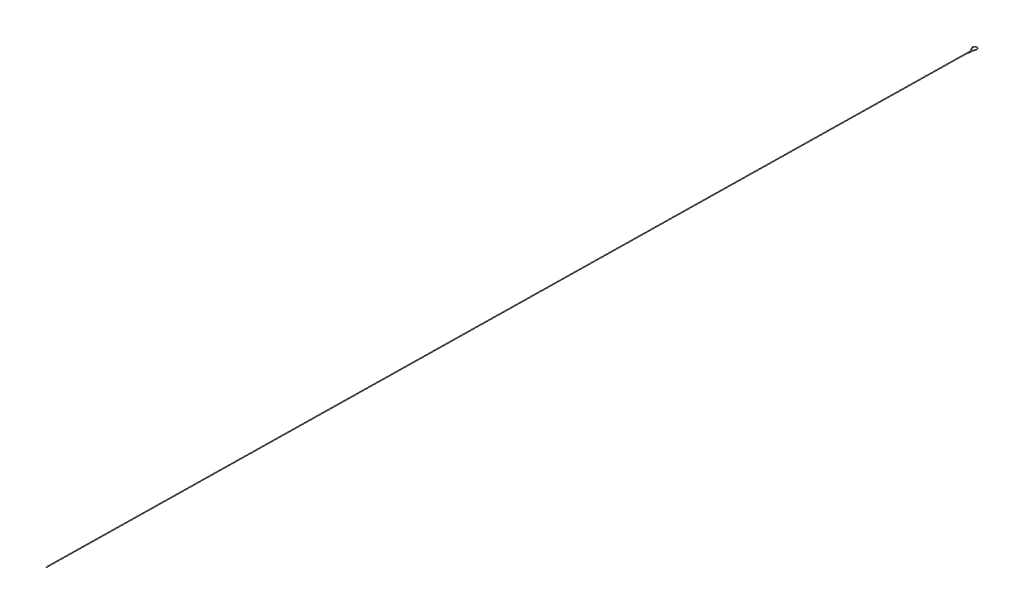
SolidWorks part; units mm, degrees
ref_plane "Front Plane" through (0, 0, 0) normal (0, 0, 1) x (1, 0, 0)
ref_plane "Top Plane" through (0, 0, 0) normal (0, 1, 0) x (1, 0, 0)
ref_plane "Right Plane" through (0, 0, 0) normal (1, 0, 0) x (0, 0, -1)
sketch "Sketch1" plane through (0, 0, 0) normal (0, 1, 0) x (1, 0, 0)
  line L0 (0, 4567.0606) -> (0, 4558.7974)
  line L2 (-10.4743, 4588.5976) -> (-1.2471, 4571.8965)
  line L3 (7.6178, 4589.0635) -> (4.4738, 4582.7755)
  line L4 (3.2, 4558.7974) -> (3.2, 4570.9408)
  line L5 (3.2, 4570.9408) -> (3.4223, 4578.5938)
  line L6 (0, 4558.7974) -> (0, 0) construction
  line L7 (0, 0) -> (-76.2, 0) construction
  line L8 (-76.2, 0) -> (-76.2, -10)
  line L9 (-76.2, 0) -> (0, 4558.7974)
  arc A0 (-4.9486, 4602.8985) -> (-3.0908, 4603.3788) centre (-0.8501, 4590.878) cw
  arc A1 (-3.0908, 4603.3788) -> (7.6178, 4589.0635) centre (-1.3265, 4593.5356) cw
  arc A2 (-4.9486, 4602.8985) -> (-10.4743, 4588.5976) centre (-1.7214, 4593.4335) ccw
  arc A5 (3.4223, 4578.5938) -> (4.4738, 4582.7755) centre (13.4181, 4578.3034) cw
  arc A6 (0, 4567.0606) -> (-1.2471, 4571.8965) centre (-10, 4567.0606) ccw
  dimension "D2" = 10
  dimension "D1" = 12.7
  dimension "D4" = 76.2
  dimension "D5" = 10
  dimension "D3" = 10
  dimension "D6" = 10
  dimension "D7" = 3.2
ref_plane "Plane3" through (0, 0, 10) normal (0, 0, 1) x (1, 0, 0)
sketch "Sketch7" plane through (0, 0, 10) normal (0, 0, 1) x (1, 0, 0)
  circle A0 centre (-76.2, 0) radius 1.575
  dimension "D1" = 3.15
sweep "Sweep5" add profiles "Sketch7" path "Sketch1"
